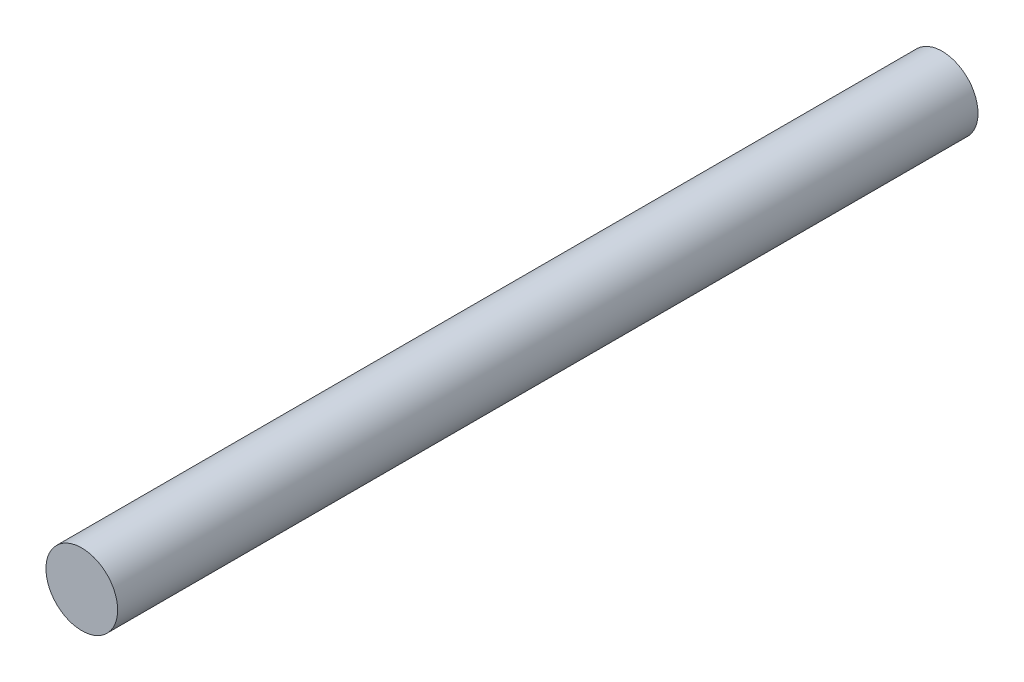
SolidWorks part; units mm, degrees
ref_plane "Front Plane" through (0, 0, 0) normal (0, 0, 1) x (1, 0, 0)
ref_plane "Top Plane" through (0, 0, 0) normal (0, 1, 0) x (1, 0, 0)
ref_plane "Right Plane" through (0, 0, 0) normal (1, 0, 0) x (0, 0, -1)
sketch "Sketch1" plane through (0, 0, 0) normal (0, 0, 1) x (1, 0, 0)
  circle A0 centre (0, 0) radius 6.35
  dimension "D1" = 12.7
extrude "Extrude1" add sketch "Sketch1" against normal mid plane 152.4
